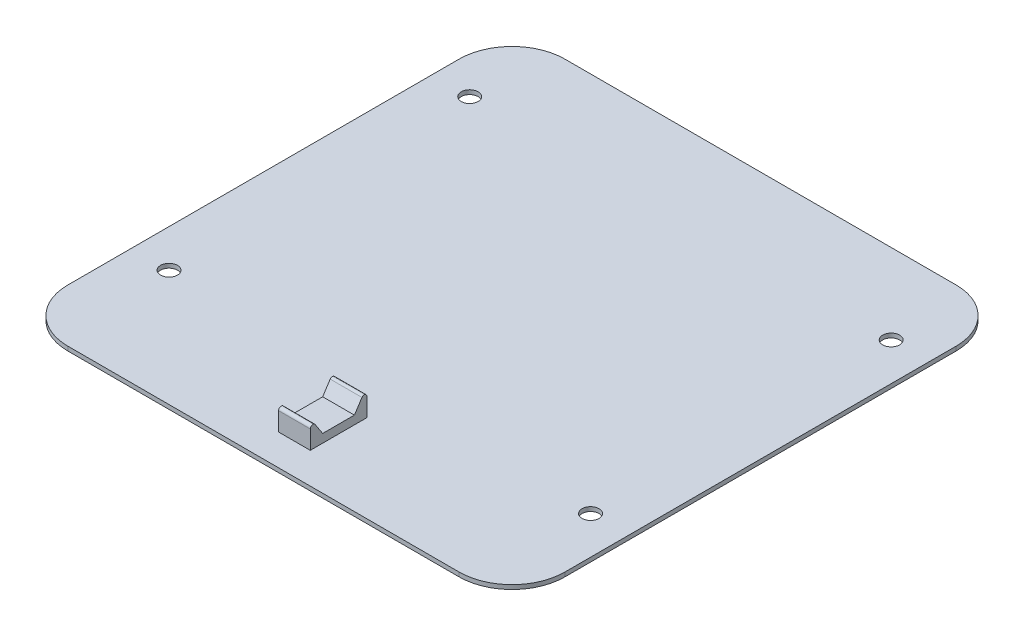
SolidWorks part; units mm, degrees
ref_plane "前视基准面" through (0, 0, 0) normal (0, 0, 1) x (1, 0, 0)
ref_plane "上视基准面" through (0, 0, 0) normal (0, 1, 0) x (1, 0, 0)
ref_plane "右视基准面" through (0, 0, 0) normal (1, 0, 0) x (0, 0, -1)
sketch "草图1" plane through (0, 0, 0) normal (0, 1, 0) x (1, 0, 0)
  line L1 (-47, 47) -> (47, 47)
  line L2 (-47, 47) -> (-47, -47)
  line L3 (-47, -47) -> (47, -47)
  line L4 (47, 47) -> (47, -47)
  line L5 (-47, 47) -> (47, -47) construction
  line L6 (-47, -47) -> (47, 47) construction
  point P0 (0, 0)
  dimension "D1" = 94
extrude "底座盖子凸台" add sketch "草图1" along normal blind 0.8
fillet "圆角1" radius 10 4 edges at (47, 0.4, -47) (47, 0.4, 47) (-47, 0.4, 47) (-47, 0.4, -47)
sketch "草图2" plane through (0, 0.8, 0) normal (0, 1, 0) x (1, 0, 0)
  line L1 (-39.85, 31.85) -> (39.85, 31.85) construction
  line L2 (-39.85, 31.85) -> (-39.85, -25) construction
  line L3 (-39.85, -25) -> (39.85, -25) construction
  line L4 (39.85, 31.85) -> (39.85, -25) construction
  line L5 (-39.85, 31.85) -> (39.85, -25) construction
  line L6 (-39.85, -25) -> (39.85, 31.85) construction
  circle A0 centre (-39.85, 31.85) radius 1.6
  circle A1 centre (39.85, 31.85) radius 1.6
  circle A2 centre (39.85, -25) radius 1.6
  circle A3 centre (-39.85, -25) radius 1.6
  point P0 (0, 3.425)
  dimension "D3" = 3.2
  dimension "D4" = 3.2
  dimension "D5" = 3.2
  dimension "D6" = 3.2
  dimension "D1" = 56.85
  dimension "D2" = 79.7
  dimension "D7" = 25
extrude "底座螺孔切除" cut sketch "草图2" against normal up to next
sketch "草图4" plane through (0, 0, 0) normal (1, 0, 0) x (0, 0, -1)
  line L0 (-41.145, 0.8) -> (-30.455, 0.8)
  line L1 (-30.455, 0.8) -> (-30.455, 5.98)
  line L2 (-30.455, 5.98) -> (-32.8, 2.4)
  line L3 (-32.8, 2.4) -> (-38.8, 2.4)
  line L4 (-38.8, 2.4) -> (-41.145, 5.98)
  line L5 (-41.145, 5.98) -> (-41.145, 0.8)
  line L6 (-23.4, 0.8) -> (-26.6, 0.8) construction
  point P8 (-35.8, 0.8)
  point P10 (-35.8, 2.4)
  point P11 (-47, 0.8)
  point P12 (0, 0)
  dimension "D1" = 10.69
  dimension "D2" = 6
  dimension "D3" = 1.6
  dimension "D4" = 5.18
  dimension "D5" = 11.2
extrude "底座电池限制凸台" add sketch "草图4" along normal mid plane 6
fillet "圆角2" radius 0.5 2 edges at (0, 5.98, 30.455) (0, 5.98, 41.145)
equation "\"squ_side\"= 94mm"
equation "\"squ_high\"= 25mm"
equation "\"squ_corner\"= 10mm"
equation "\"squ_thickness\"= 2mm"
equation "\"sw_thickness\"= 8mm"
equation "\"sw_width\"= 13.5mm"
equation "\"sw_high\"= 8.9mm"
equation "\"touch_thickness\"= 1.1mm"
equation "\"touch_side\"= 23.6mm"
equation "\"battery_diameter\"= 18.4mm"
equation "\"battery_length\"= 66.4mm"
equation "\"battery_thickness\"= 0.8mm"
equation "\"conch_length\"= 52mm"
equation "\"conch_width\"= 36mm"
equation "\"nut_side\"= 2.8mm"
equation "\"nut_distance\"= 2mm"
equation "\"nut_squ\"= 5mm"
equation "\"conch_high\"= 6.19mm"
equation "\"nut_high\"= 4mm"
equation "\"nut_side_err\"= \"nut_side\" + 0.4mm"
equation "\"bottom_length\"= 30mm"
equation "\"bottom_width\"= 25mm"
equation "\"battery_length_err\"= \"battery_length\" + 3.0mm"
equation "\"D1@草图1\"=\"squ_side\""
equation "\"D1@圆角1\"=\"squ_corner\""
equation "\"cover_thickness\"= 0.8mm"
equation "\"D1@底座盖子凸台\"=\"cover_thickness\""
equation "\"nut_radius\"= 3.2mm"
equation "\"D3@草图2\"=\"nut_radius\""
equation "\"D4@草图2\"=\"nut_radius\""
equation "\"D5@草图2\"=\"nut_radius\""
equation "\"D6@草图2\"=\"nut_radius\""
equation "\"battery_distance\"= 1.6mm"
equation "\"battery_head_width\"= 6mm"
equation "\"battery_tail_width\"= 10.69mm"
equation "\"D1@草图4\"=\"battery_tail_width\""
equation "\"D2@草图4\"=\"battery_head_width\""
equation "\"D3@草图4\"=\"battery_distance\""
equation "\"battery_tail_distance\"= 5.18mm"
equation "\"D4@草图4\"=\"battery_tail_distance\""
